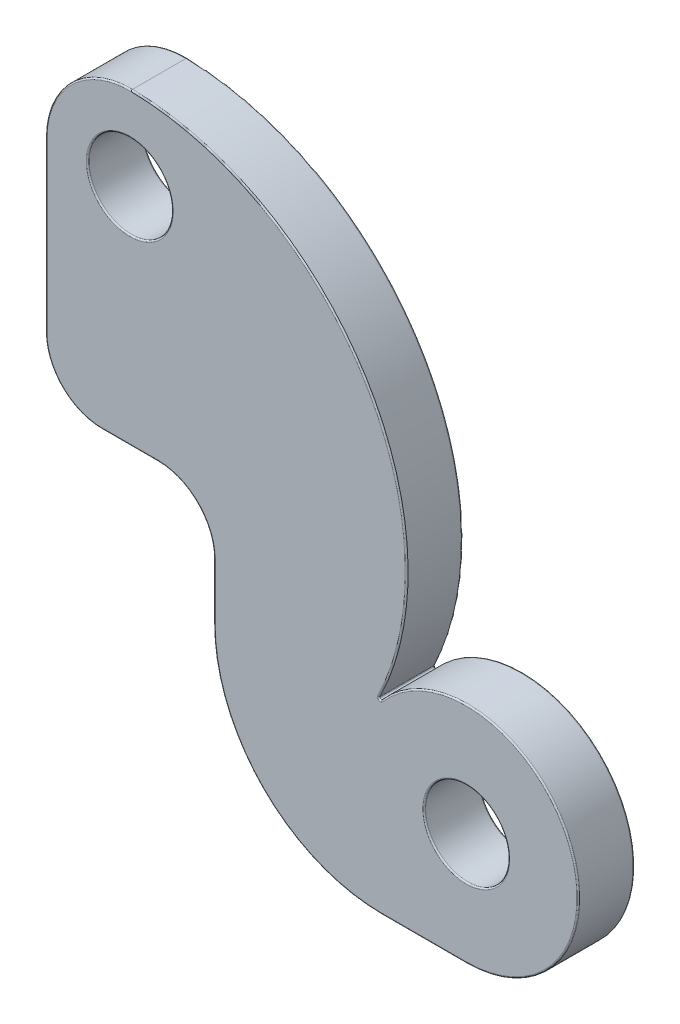
SolidWorks part; units mm, degrees
ref_plane "Front Plane" through (0, 0, 0) normal (0, 0, 1) x (1, 0, 0)
ref_plane "Top Plane" through (0, 0, 0) normal (0, 1, 0) x (1, 0, 0)
ref_plane "Right Plane" through (0, 0, 0) normal (1, 0, 0) x (0, 0, -1)
sketch "Sketch1" plane through (0, 0, 0) normal (0, 0, 1) x (1, 0, 0)
  line L0 (0, 0) -> (0, 19059.3068) construction
  line L1 (0, 0) -> (19059.3068, 0) construction
  line L2 (-15, 0) -> (-15, -30)
  line L3 (-5, -40) -> (5, -40)
  line L4 (15, -50) -> (15, -60)
  line L5 (45, -90) -> (60, -90)
  circle A0 centre (0, 0) radius 7.5
  arc A1 (0.2651, 14.9977) -> (-15, 0) centre (0, 0) ccw
  circle A2 centre (60, -70) radius 7.5
  arc A3 (60, -90) -> (42.6804, -59.9984) centre (60, -70) ccw
  arc A4 (5, -40) -> (15, -50) centre (5, -50) cw
  arc A5 (-15, -30) -> (-5, -40) centre (-5, -30) ccw
  arc A6 (15, -60) -> (45, -90) centre (45, -60) ccw
  arc A7 (0.2651, 14.9977) -> (42.6804, -59.9984) centre (-0.6186, -34.9945) cw
  point P20 (-15, -40)
  point P23 (15, -90)
  point P27 (0, 0)
  dimension "D1" = 30
  dimension "D2" = 15
  dimension "D3" = 40
  dimension "D4" = 15
  dimension "D9" = 10
  dimension "D10" = 30
  dimension "D11" = 50
  dimension "D5" = 60
  dimension "D6" = 70
  dimension "D7" = 45
  dimension "D8" = 40
extrude "Boss-Extrude1" add sketch "Sketch1" along normal blind 10
fillet "Fillet1" radius 0.25 25 edges at (42.6804, -59.9984, 5) (42.903, -10.3802, 10) (77.321, -60.0008, 10) (52.5, -90, 10) (23.7868, -81.2132, 10) (15, -55, 10) (12.0711, -42.9289, 10) (0, -40, 10) (-12.0711, -37.0711, 10) (-15, -15, 10) (-10.5124, 10.6999, 10) (42.903, -10.3802, 0) (77.321, -60.0008, 0) (52.5, -90, 0) (23.7868, -81.2132, 0) (15, -55, 0) (12.0711, -42.9289, 0) (0, -40, 0) (-12.0711, -37.0711, 0) (-15, -15, 0) (-10.5124, 10.6999, 0) (7.5, 0, 10) (7.5, 0, 0) (67.5, -70, 10) (67.5, -70, 0)
